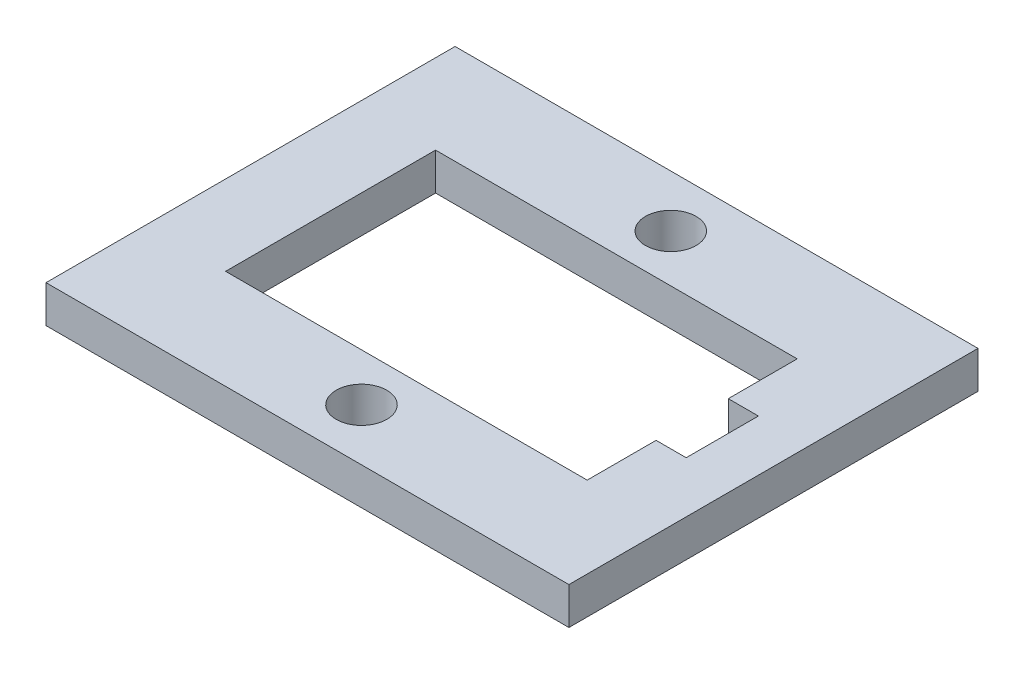
SolidWorks part; units mm, degrees
ref_plane "Front Plane" through (0, 0, 0) normal (0, 0, 1) x (1, 0, 0)
ref_plane "Top Plane" through (0, 0, 0) normal (0, 1, 0) x (1, 0, 0)
ref_plane "Right Plane" through (0, 0, 0) normal (1, 0, 0) x (0, 0, -1)
sketch "Sketch2" plane through (0, 0, 0) normal (0, 1, 0) x (1, 0, 0)
  line L0 (-12.329, 7.8335) -> (11.9606, 7.8335)
  line L1 (-17.7015, 14.5166) -> (17.4229, 14.5166)
  line L2 (-17.7015, 14.5166) -> (-17.7015, -12.9616)
  line L3 (-17.7015, -12.9616) -> (17.4229, -12.9616)
  line L4 (17.4229, 14.5166) -> (17.4229, -12.9616)
  line L5 (11.9606, 7.8335) -> (11.9606, 3.2059)
  line L6 (11.9606, 3.2059) -> (13.9825, 3.2059)
  line L7 (13.9825, 3.2059) -> (13.9825, -1.6439)
  line L8 (13.9825, -1.6439) -> (11.9606, -1.6439)
  line L9 (11.9606, -1.6439) -> (11.9606, -6.2716)
  line L10 (11.9606, -6.2716) -> (-12.329, -6.2716)
  line L11 (-12.329, -6.2716) -> (-12.329, 7.8335)
  circle A0 centre (0.2754, 11.0289) radius 1.7
  circle A1 centre (0, -9.4716) radius 1.7
  point P16 (0, 0)
  point P17 (0, 0)
  dimension "D8" = 3.4
  dimension "D2" = 5.3725
  dimension "D3" = 4.6277
  dimension "D4" = 24.2896
  dimension "D5" = 2.0219
  dimension "D6" = 4.8498
  dimension "D7" = 3.4877
  dimension "D9" = 3.1953
  dimension "D10" = 3.49
  dimension "D11" = 3.2
  dimension "D12" = 3.4404
extrude "Boss-Extrude2" add sketch "Sketch2" along normal blind 2.5
